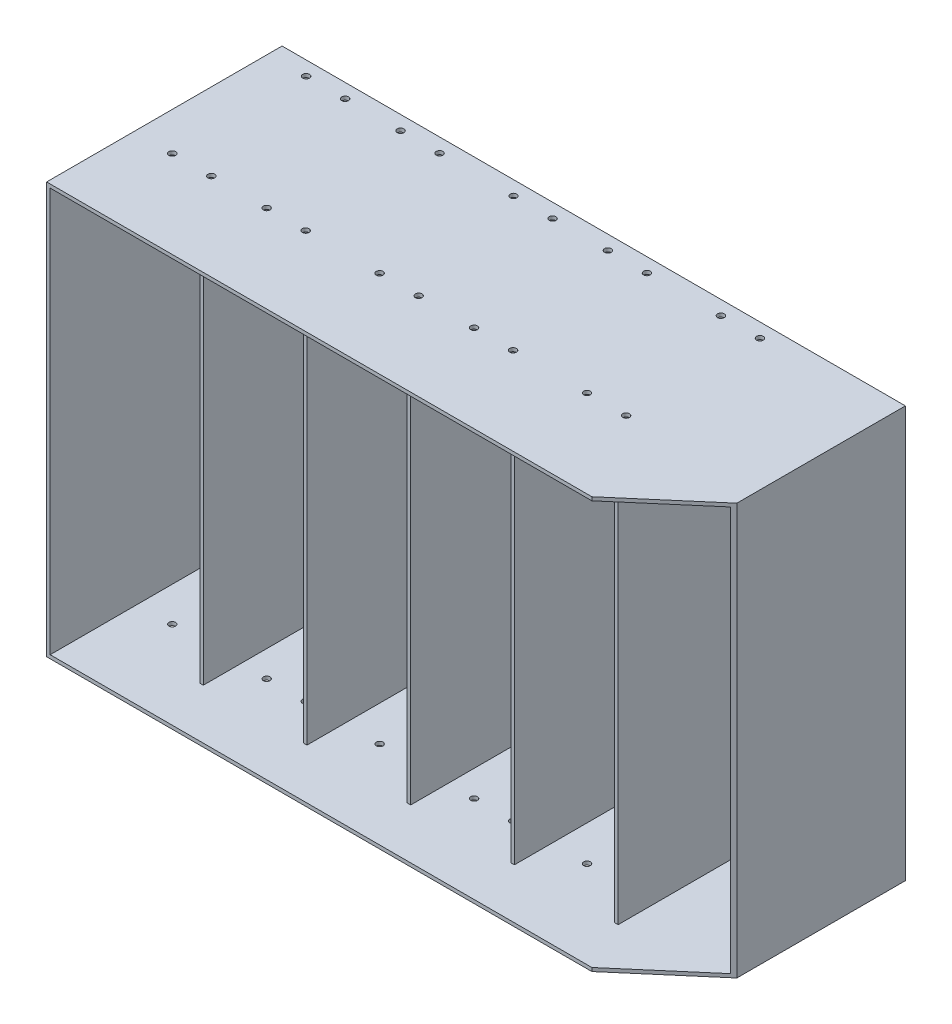
SolidWorks part; units mm, degrees
material "Custom Plastic"
ref_plane "X-Y Datum" through (0, 0, 0) normal (0, 0, 1) x (1, 0, 0)
ref_plane "X-Z Datum" through (0, 0, 0) normal (0, 1, 0) x (1, 0, 0)
ref_plane "Y-Z Datum" through (0, 0, 0) normal (1, 0, 0) x (0, 0, -1)
sketch "Sketch1" plane through (0, 0, 0) normal (0, 0, 1) x (1, 0, 0)
  line L0 (-276.225, 0) -> (276.225, 0) construction
  line L1 (-276.225, 181.1563) -> (276.225, 181.1563)
  line L2 (-276.225, 181.1563) -> (-276.225, -181.1563)
  line L3 (-276.225, -181.1563) -> (276.225, -181.1563)
  line L4 (276.225, 181.1563) -> (276.225, -181.1563)
  line L5 (-276.225, 181.1563) -> (276.225, -181.1563) construction
  line L6 (-276.225, -181.1563) -> (276.225, 181.1563) construction
  line L7 (-273.8438, 178.775) -> (-190.2437, 178.775) construction
  line L8 (-273.8438, 178.775) -> (-273.8438, -178.775) construction
  line L9 (-273.8438, -178.775) -> (-190.2437, -178.775) construction
  line L10 (-190.2437, 178.775) -> (-190.2437, -178.775) construction
  line L11 (-273.8438, 178.775) -> (-190.2437, -178.775) construction
  line L12 (-273.8438, -178.775) -> (-190.2437, 178.775) construction
  line L13 (-187.0687, -181.1563) -> (-187.0687, 181.1563)
  line L14 (-279.4, 184.3313) -> (279.4, 184.3313)
  line L15 (279.4, 184.3313) -> (279.4, -184.3313)
  line L16 (-279.4, -184.3313) -> (279.4, -184.3313)
  line L17 (-279.4, 184.3313) -> (-279.4, -184.3313)
  line L18 (-183.8937, -181.1563) -> (-183.8937, 181.1563)
  line L19 (-187.0687, 0) -> (-183.8937, 0) construction
  line L20 (-180.8797, 178.775) -> (-180.8797, -178.775) construction
  line L21 (-180.8797, 178.775) -> (-97.2797, 178.775) construction
  line L22 (-97.2797, 178.775) -> (-97.2797, -178.775) construction
  line L23 (-180.8797, -178.775) -> (-97.2797, -178.775) construction
  line L24 (-94.1047, -181.1563) -> (-94.1047, 181.1563)
  line L25 (-90.9297, -181.1563) -> (-90.9297, 181.1563)
  line L26 (-87.9157, 178.775) -> (-87.9157, -178.775) construction
  line L27 (-87.9157, 178.775) -> (-4.3157, 178.775) construction
  line L28 (-4.3157, 178.775) -> (-4.3157, -178.775) construction
  line L29 (-87.9157, -178.775) -> (-4.3157, -178.775) construction
  line L30 (-1.1407, -181.1563) -> (-1.1407, 181.1563)
  line L31 (2.0343, -181.1563) -> (2.0343, 181.1563)
  line L32 (5.0483, 178.775) -> (5.0483, -178.775) construction
  line L33 (5.0483, 178.775) -> (88.6483, 178.775) construction
  line L34 (88.6483, 178.775) -> (88.6483, -178.775) construction
  line L35 (5.0483, -178.775) -> (88.6483, -178.775) construction
  line L36 (91.8233, -181.1563) -> (91.8233, 181.1563)
  line L37 (94.9983, -181.1563) -> (94.9983, 181.1563)
  line L38 (98.0123, 178.775) -> (98.0123, -178.775) construction
  line L39 (98.0123, 178.775) -> (181.6123, 178.775) construction
  line L40 (181.6123, 178.775) -> (181.6123, -178.775) construction
  line L41 (98.0123, -178.775) -> (181.6123, -178.775) construction
  line L42 (184.7873, -181.1563) -> (184.7873, 181.1563)
  line L43 (187.9623, -181.1563) -> (187.9623, 181.1563)
  line L44 (-180.8797, -178.775) -> (-97.2797, 178.775) construction
  line L45 (-180.8797, 178.775) -> (-97.2797, -178.775) construction
  line L46 (-87.9157, -178.775) -> (-4.3157, 178.775) construction
  line L47 (-87.9157, 178.775) -> (-4.3157, -178.775) construction
  line L48 (5.0483, -178.775) -> (88.6483, 178.775) construction
  line L49 (5.0483, 178.775) -> (88.6483, -178.775) construction
  line L50 (98.0123, -178.775) -> (181.6123, 178.775) construction
  line L51 (98.0123, 178.775) -> (181.6123, -178.775) construction
  point P0 (0, 0)
  point P6 (-232.0437, 0)
  point P23 (-185.4812, 0)
  point P24 (-139.0797, 0)
  dimension "D1" = 357.55
  dimension "D2" = 83.6
  dimension "D3" = 2.3813
  dimension "D4" = 2.3813
  dimension "D5" = 3.175
  dimension "D8" = 46.5625
  dimension "D10" = 558.8
  dimension "D12" = 92.964
  dimension "D6" = 3.175
  dimension "D7" = 3.175
  dimension "D9" = 5
  dimension "D11" = 5
extrude "Boss-Extrude1" add sketch "Sketch1" along normal blind 3.175 contours L3 L13 L1 L2 | L3 L24 L1 L18 | L3 L18 L1 L13 | L14 L17 L16 L15 L1 L4 L3 L2 | L3 L30 L1 L25 | L3 L25 L1 L24 | L3 L36 L1 L31 | L3 L31 L1 L30 | L3 L42 L1 L37 | L3 L37 L1 L36 | L43 L3 L4 L1 | L3 L43 L1 L42
sketch "Sketch2" plane through (0, 0, 3.175) normal (0, 0, 1) x (1, 0, 0)
  line L0 (-187.0687, -181.1563) -> (-187.0687, 181.1563) construction
  line L1 (-94.1047, -181.1563) -> (-94.1047, 181.1563) construction
  line L2 (-183.8937, -181.1563) -> (-183.8937, 181.1563) construction
  line L3 (91.8233, -181.1563) -> (91.8233, 181.1563) construction
  line L4 (276.225, 181.1563) -> (-276.225, 181.1563)
  line L5 (276.225, -181.1563) -> (276.225, 181.1563)
  line L6 (-276.225, -181.1563) -> (276.225, -181.1563)
  line L7 (-276.225, 181.1563) -> (-276.225, -181.1563)
  line L8 (276.225, 181.1563) -> (-276.225, 181.1563)
  line L9 (276.225, -181.1563) -> (276.225, 181.1563)
  line L10 (-276.225, -181.1563) -> (276.225, -181.1563)
  line L11 (-276.225, 181.1563) -> (-276.225, -181.1563)
  line L12 (-279.4, -184.3313) -> (279.4, -184.3313)
  line L13 (-279.4, 184.3313) -> (-279.4, -184.3313)
  line L14 (279.4, 184.3313) -> (-279.4, 184.3313)
  line L15 (279.4, -184.3313) -> (279.4, 184.3313)
  line L16 (-279.4, -184.3313) -> (279.4, -184.3313)
  line L17 (-279.4, 184.3313) -> (-279.4, -184.3313)
  line L18 (279.4, 184.3313) -> (-279.4, 184.3313)
  line L19 (279.4, -184.3313) -> (279.4, 184.3313)
  line L20 (2.0343, -181.1563) -> (2.0343, 181.1563) construction
  line L21 (-1.1407, -181.1563) -> (-1.1407, 181.1563) construction
  line L22 (-90.9297, -181.1563) -> (-90.9297, 181.1563) construction
  line L23 (187.9623, -181.1563) -> (187.9623, 181.1563) construction
  line L24 (184.7873, -181.1563) -> (184.7873, 181.1563) construction
  line L25 (94.9983, -181.1563) -> (94.9983, 181.1563) construction
  line L26 (-187.0687, -181.1563) -> (-187.0687, 181.1563)
  line L27 (-94.1047, -181.1563) -> (-94.1047, 181.1563)
  line L28 (-183.8937, -181.1563) -> (-183.8937, 181.1563)
  line L29 (91.8233, -181.1563) -> (91.8233, 181.1563)
  line L30 (2.0343, -181.1563) -> (2.0343, 181.1563)
  line L31 (-1.1407, -181.1563) -> (-1.1407, 181.1563)
  line L32 (-90.9297, -181.1563) -> (-90.9297, 181.1563)
  line L33 (187.9623, -181.1563) -> (187.9623, 181.1563)
  line L34 (184.7873, -181.1563) -> (184.7873, 181.1563)
  line L35 (94.9983, -181.1563) -> (94.9983, 181.1563)
  line M9 (279.4, 184.3313) -> (-279.4, 184.3313)
  line M10 (-279.4, 184.3313) -> (-279.4, -184.3313)
  line M11 (-279.4, -184.3313) -> (279.4, -184.3313)
  line M12 (279.4, -184.3313) -> (279.4, 184.3313)
  dimension "D1" = 0
  dimension "D2" = 0
extrude "Boss-Extrude2" add sketch "Sketch2" along normal blind 162.9 contours L11 L8 L9 L10 M12 M9 M10 M11 | L10 L28 L8 L26 | L10 L32 L8 L27 | L31 L10 L30 L8 | L10 L35 L8 L29 | L34 L10 L33 L8
sketch "Sketch3" plane through (0, 0, 166.075) normal (0, 0, 1) x (1, 0, 0)
  line L0 (-187.0687, -181.1563) -> (-187.0687, 181.1563) construction
  line L1 (-94.1047, -181.1563) -> (-94.1047, 181.1563) construction
  line L2 (-183.8937, -181.1563) -> (-183.8937, 181.1563) construction
  line L3 (91.8233, -181.1563) -> (91.8233, 181.1563) construction
  line L4 (276.225, 181.1563) -> (-276.225, 181.1563)
  line L5 (276.225, -181.1563) -> (276.225, 181.1563)
  line L6 (-276.225, -181.1563) -> (276.225, -181.1563)
  line L7 (-276.225, 181.1563) -> (-276.225, -181.1563)
  line L8 (276.225, 181.1563) -> (-276.225, 181.1563)
  line L9 (276.225, -181.1563) -> (276.225, 181.1563)
  line L10 (-276.225, -181.1563) -> (276.225, -181.1563)
  line L11 (-276.225, 181.1563) -> (-276.225, -181.1563)
  line L12 (-279.4, -184.3313) -> (279.4, -184.3313)
  line L13 (-279.4, 184.3313) -> (-279.4, -184.3313)
  line L14 (279.4, 184.3313) -> (-279.4, 184.3313)
  line L15 (279.4, -184.3313) -> (279.4, 184.3313)
  line L16 (-279.4, -184.3313) -> (279.4, -184.3313)
  line L17 (-279.4, 184.3313) -> (-279.4, -184.3313)
  line L18 (279.4, 184.3313) -> (-279.4, 184.3313)
  line L19 (279.4, -184.3313) -> (279.4, 184.3313)
  line L20 (2.0343, -181.1563) -> (2.0343, 181.1563) construction
  line L21 (-1.1407, -181.1563) -> (-1.1407, 181.1563) construction
  line L22 (-90.9297, -181.1563) -> (-90.9297, 181.1563) construction
  line L23 (187.9623, -181.1563) -> (187.9623, 181.1563) construction
  line L24 (184.7873, -181.1563) -> (184.7873, 181.1563) construction
  line L25 (94.9983, -181.1563) -> (94.9983, 181.1563) construction
  line L26 (-187.0687, -181.1563) -> (-187.0687, 181.1563)
  line L27 (-94.1047, -181.1563) -> (-94.1047, 181.1563)
  line L28 (-183.8937, -181.1563) -> (-183.8937, 181.1563)
  line L29 (91.8233, -181.1563) -> (91.8233, 181.1563)
  line L30 (2.0343, -181.1563) -> (2.0343, 181.1563)
  line L31 (-1.1407, -181.1563) -> (-1.1407, 181.1563)
  line L32 (-90.9297, -181.1563) -> (-90.9297, 181.1563)
  line L33 (187.9623, -181.1563) -> (187.9623, 181.1563)
  line L34 (184.7873, -181.1563) -> (184.7873, 181.1563)
  line L35 (94.9983, -181.1563) -> (94.9983, 181.1563)
  line M9 (94.9983, 181.1563) -> (184.7873, 181.1563)
  line M11 (184.7873, -181.1563) -> (94.9983, -181.1563)
  line M13 (2.0343, 181.1563) -> (91.8233, 181.1563)
  line M15 (91.8233, -181.1563) -> (2.0343, -181.1563)
  line M17 (-90.9297, 181.1563) -> (-1.1407, 181.1563)
  line M19 (-1.1407, -181.1563) -> (-90.9297, -181.1563)
  line M21 (-183.8937, 181.1563) -> (-94.1047, 181.1563)
  line M23 (-94.1047, -181.1563) -> (-183.8937, -181.1563)
  line M25 (-276.225, 181.1563) -> (-187.0687, 181.1563)
  line M27 (-187.0687, -181.1563) -> (-276.225, -181.1563)
  line M28 (-276.225, -181.1563) -> (-276.225, 181.1563)
  line M30 (187.9623, 181.1563) -> (276.225, 181.1563)
  line M31 (276.225, 181.1563) -> (276.225, -181.1563)
  line M32 (276.225, -181.1563) -> (187.9623, -181.1563)
  line M33 (279.4, -184.3313) -> (279.4, 184.3313)
  line M34 (279.4, 184.3313) -> (-279.4, 184.3313)
  line M35 (-279.4, 184.3313) -> (-279.4, -184.3313)
  line M36 (-279.4, -184.3313) -> (279.4, -184.3313)
  dimension "D1" = 0
  dimension "D2" = 0
extrude "Boss-Extrude3" add sketch "Sketch3" along normal blind 45 contours L10 L8 M36 M33 M34 M35 M27 M28 M25 M21 M17 M13 M9 M30 M31 M32 M11 M15 M19 M23
sketch "Sketch4" plane through (0, -184.3313, 0) normal (0, -1, 0) x (1, 0, 0)
  line L0 (209.4, 211.075) -> (279.4, 151.075)
  line L1 (-279.4, 211.075) -> (279.4, 211.075) construction
  line L2 (279.4, 211.075) -> (279.4, 0) construction
  line M3 (279.4, 0) -> (279.4, 211.075)
  line M4 (279.4, 211.075) -> (-279.4, 211.075)
  dimension "D1" = 60
  dimension "D2" = 70
extrude "Cut-Extrude1" cut sketch "Sketch4" against normal through all contours L0 M4 M3
sketch "Sketch5" plane through (0, -184.3313, 0) normal (0, -1, 0) x (1, 0, 0)
  circle A0 centre (-210.1469, 12.7) radius 3 construction
  circle A1 centre (-245.1469, 12.7) radius 3 construction
  circle A2 centre (-210.1469, 132.7) radius 3 construction
  circle A3 centre (-245.1469, 132.7) radius 3 construction
  circle A4 centre (-210.1469, 12.7) radius 3
  circle A5 centre (-245.1469, 12.7) radius 3
  circle A6 centre (-210.1469, 132.7) radius 3
  circle A7 centre (-245.1469, 132.7) radius 3
extrude "Cut-Extrude2" cut sketch "Sketch5" against normal through all
pattern_linear "LPattern1" count 3 spacing 185.928 along (1, 0, 0) of "Cut-Extrude2"
sketch "Sketch6" plane through (0, -184.3313, 0) normal (0, -1, 0) x (1, 0, 0)
  circle A0 centre (-125.4993, 132.7) radius 3 construction
  circle A1 centre (-160.4993, 132.7) radius 3 construction
  circle A2 centre (-125.4993, 12.7) radius 3 construction
  circle A3 centre (-160.4993, 12.7) radius 3 construction
  circle A4 centre (-125.4993, 132.7) radius 3
  circle A5 centre (-160.4993, 132.7) radius 3
  circle A6 centre (-125.4993, 12.7) radius 3
  circle A7 centre (-160.4993, 12.7) radius 3
extrude "Cut-Extrude3" cut sketch "Sketch6" against normal through all
pattern_linear "LPattern2" count 2 spacing 185.928 along (1, 0, 0) of "Cut-Extrude3"
